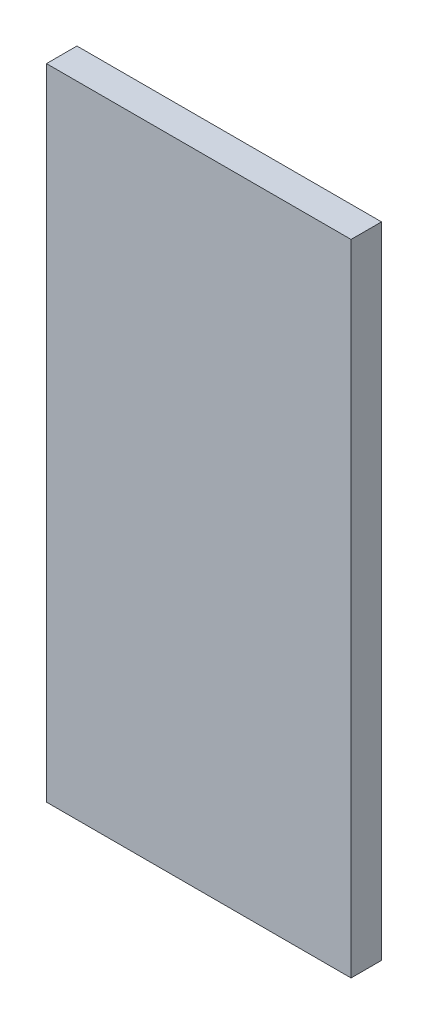
SolidWorks part; units mm, degrees
ref_plane "Front Plane" through (0, 0, 0) normal (0, 0, 1) x (1, 0, 0)
ref_plane "Top Plane" through (0, 0, 0) normal (0, 1, 0) x (1, 0, 0)
ref_plane "Right Plane" through (0, 0, 0) normal (1, 0, 0) x (0, 0, -1)
sketch "Sketch1" plane through (0, 0, 0) normal (0, 0, 1) x (1, 0, 0)
  line L1 (0, 0) -> (100, 0)
  line L2 (0, 0) -> (0, 210)
  line L3 (0, 210) -> (100, 210)
  line L4 (100, 0) -> (100, 210)
  dimension "D1" = 100
  dimension "D2" = 210
extrude "Boss-Extrude1" add sketch "Sketch1" along normal blind 10
sketch "Sketch2" plane through (0, 0, 10) normal (0, 0, 1) x (1, 0, 0)
  line L0 (100, 210) -> (0, 210) construction
  line L1 (5.5, 0) -> (-5.5, 0) construction
  line L2 (50, 210) -> (50, 0) construction
  circle A0 centre (50, 155) radius 45
  circle A1 centre (50, 55) radius 45
  dimension "D1" = 90
  dimension "D2" = 55
  dimension "D3" = 55
